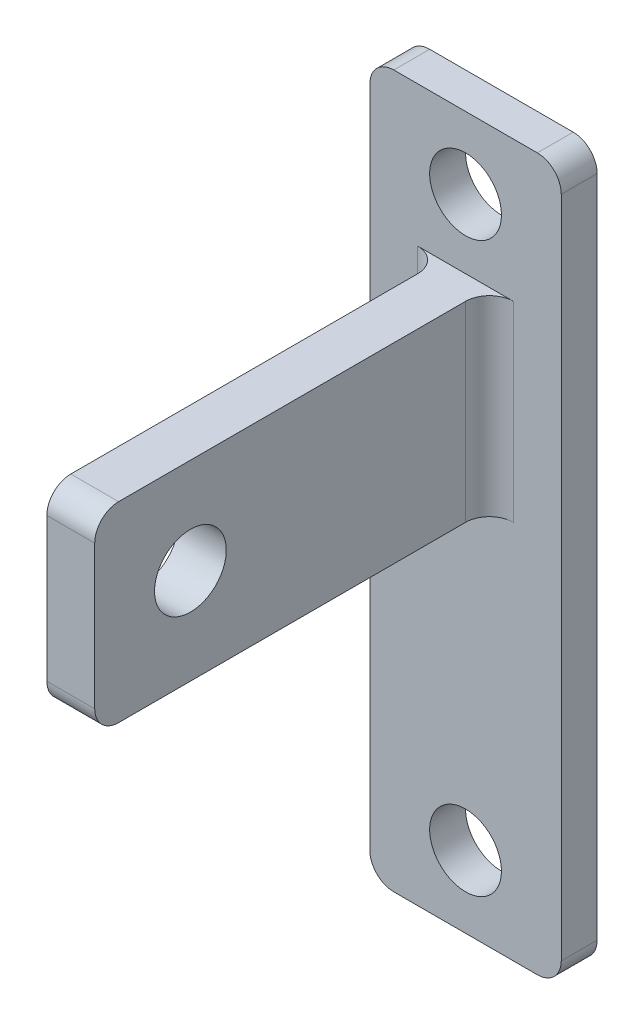
SolidWorks part; units mm, degrees
ref_plane "前视基准面" through (0, 0, 0) normal (0, 0, 1) x (1, 0, 0)
ref_plane "上视基准面" through (0, 0, 0) normal (0, 1, 0) x (1, 0, 0)
ref_plane "右视基准面" through (0, 0, 0) normal (1, 0, 0) x (0, 0, -1)
sketch "草图1" plane through (0, 0, 0) normal (0, 0, 1) x (1, 0, 0)
  line L0 (0, 11.875) -> (0, -11.875) construction
  line L1 (-4, -14.875) -> (4, -14.875)
  line L2 (-4, -14.875) -> (-4, 14.875)
  line L3 (-4, 14.875) -> (4, 14.875)
  line L4 (4, -14.875) -> (4, 14.875)
  line L5 (-4, -14.875) -> (4, 14.875) construction
  line L6 (-4, 14.875) -> (4, -14.875) construction
  circle A0 centre (0, 11.875) radius 1.5
  circle A1 centre (0, -11.875) radius 1.5
  point P0 (0, 0)
  point P12 (0, 0)
  dimension "D1" = 3
  dimension "D2" = 3
  dimension "D3" = 8
  dimension "D4" = 23.75
  dimension "D5" = 3
extrude "凸台-拉伸1" add sketch "草图1" along normal blind 1.5
sketch "草图2" plane through (0, 0, 1.5) normal (0, 0, 1) x (1, 0, 0)
  line L1 (-1, 1) -> (1, 1)
  line L2 (-1, 1) -> (-1, 9)
  line L3 (-1, 9) -> (1, 9)
  line L4 (1, 1) -> (1, 9)
  line L5 (-1, 1) -> (1, 9) construction
  line L6 (-1, 9) -> (1, 1) construction
  point P0 (0, 5)
  dimension "D1" = 2
  dimension "D2" = 8
  dimension "D3" = 5
extrude "凸台-拉伸2" add sketch "草图2" along normal blind 16.5
fillet "圆角1" radius 1 2 edges at (-1, 5, 1.5) (1, 5, 1.5)
fillet "圆角2" radius 1 6 edges at (4, -14.875, 0.75) (-4, -14.875, 0.75) (4, 14.875, 0.75) (-4, 14.875, 0.75) (0, 1, 18) (0, 9, 18)
sketch "草图4" plane through (-1, 0, 0) normal (-1, 0, 0) x (0, 0, 1)
  line L0 (18, 5) -> (1.5, 5) construction
  line L1 (18, 8) -> (18, 2) construction
  line L2 (1.5, 1) -> (1.5, 9) construction
  line L3 (18, 2) -> (18, 8) construction
  circle A0 centre (14, 5) radius 1.5
  point P8 (9.75, 5)
  dimension "D1" = 3
  dimension "D2" = 4
extrude "切除-拉伸1" cut sketch "草图4" against normal blind 2
